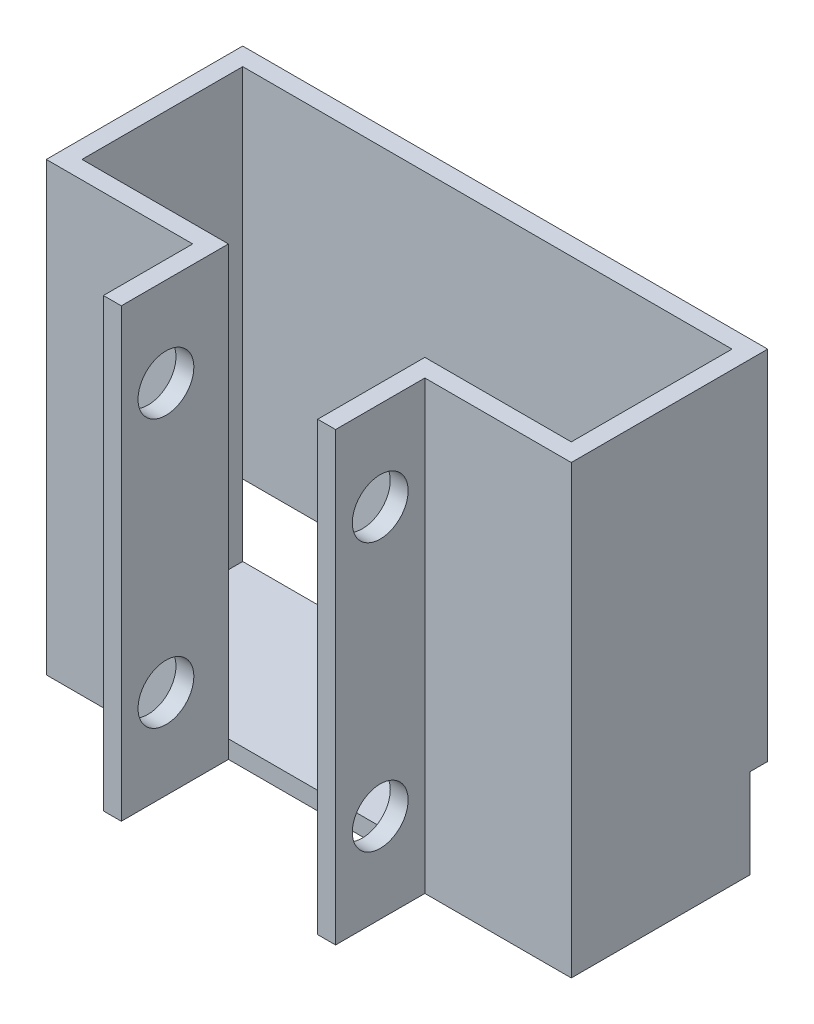
SolidWorks part; units mm, degrees
ref_plane "Front Plane" through (0, 0, 0) normal (0, 0, 1) x (1, 0, 0)
ref_plane "Top Plane" through (0, 0, 0) normal (0, 1, 0) x (1, 0, 0)
ref_plane "Right Plane" through (0, 0, 0) normal (1, 0, 0) x (0, 0, -1)
sketch "Sketch1" plane through (0, 0, 0) normal (0, 0, 1) x (1, 0, 0)
  line L1 (-35.9936, 30.5476) -> (38.6824, 30.5476)
  line L2 (-35.9936, 30.5476) -> (-35.9936, -32.9524)
  line L3 (-35.9936, -32.9524) -> (38.6824, -32.9524)
  line L4 (38.6824, 30.5476) -> (38.6824, -32.9524)
  dimension "D1" = 74.676
  dimension "D2" = 63.5
extrude "Boss-Extrude1" add sketch "Sketch1" along normal blind 27.94
sketch "Sketch2" plane through (0, 30.5476, 0) normal (0, 1, 0) x (1, 0, 0)
  line L0 (38.6824, 0) -> (-35.9936, 0) construction
  line L1 (36.1424, -25.4) -> (-33.4536, -25.4)
  line L2 (36.1424, -25.4) -> (36.1424, -2.54)
  line L3 (36.1424, -2.54) -> (-33.4536, -2.54)
  line L4 (-33.4536, -25.4) -> (-33.4536, -2.54)
  line L5 (-35.9936, -27.94) -> (-35.9936, 0) construction
  line L6 (38.6824, -27.94) -> (-35.9936, -27.94) construction
  line L7 (38.6824, -27.94) -> (38.6824, 0) construction
  dimension "D1" = 2.54
  dimension "D2" = 2.54
  dimension "D3" = 2.54
  dimension "D4" = 2.54
extrude "Cut-Extrude1" cut sketch "Sketch2" against normal blind 60.96
sketch "Sketch3" plane through (0, 0, 27.94) normal (0, 0, 1) x (1, 0, 0)
  line L0 (38.6824, 30.5476) -> (-35.9936, 30.5476) construction
  line L1 (-12.6256, 30.5476) -> (15.3144, 30.5476)
  line L2 (-12.6256, 30.5476) -> (-12.6256, -32.9524)
  line L3 (-12.6256, -32.9524) -> (15.3144, -32.9524)
  line L4 (15.3144, 30.5476) -> (15.3144, -32.9524)
  line L7 (38.6824, -32.9524) -> (38.6824, 30.5476) construction
  line L8 (-35.9936, -32.9524) -> (38.6824, -32.9524) construction
  dimension "D1" = 27.94
  dimension "D2" = 23.368
extrude "Cut-Extrude2" cut sketch "Sketch3" against normal blind 2.54
sketch "Sketch4" plane through (0, 0, 0) normal (0, 0, -1) x (-1, 0, 0)
  line L0 (35.9936, 30.5476) -> (35.9936, -32.9524) construction
  line L1 (-38.6824, -32.9524) -> (35.9936, -32.9524)
  line L2 (-38.6824, -32.9524) -> (-38.6824, -20.2524)
  line L3 (-38.6824, -20.2524) -> (35.9936, -20.2524)
  line L4 (35.9936, -32.9524) -> (35.9936, -20.2524)
  dimension "D1" = 12.7
extrude "Cut-Extrude3" cut sketch "Sketch4" against normal blind 2.54
sketch "Sketch5" plane through (0, 0, 27.94) normal (0, 0, 1) x (1, 0, 0)
  line L0 (-35.9936, -32.9524) -> (-12.6256, -32.9524) construction
  line L1 (-12.6256, 30.5476) -> (-15.1656, 30.5476)
  line L2 (-12.6256, 30.5476) -> (-12.6256, -32.9524)
  line L3 (-12.6256, -32.9524) -> (-15.1656, -32.9524)
  line L4 (-15.1656, 30.5476) -> (-15.1656, -32.9524)
  line L5 (15.3144, -32.9524) -> (38.6824, -32.9524) construction
  line L6 (15.3144, 30.5476) -> (17.8544, 30.5476)
  line L7 (15.3144, 30.5476) -> (15.3144, -32.9524)
  line L8 (15.3144, -32.9524) -> (17.8544, -32.9524)
  line L9 (17.8544, 30.5476) -> (17.8544, -32.9524)
  dimension "D1" = 2.54
  dimension "D2" = 2.54
extrude "Boss-Extrude2" add sketch "Sketch5" along normal blind 12.7
sketch "Sketch6" plane through (-15.1656, 0, 0) normal (-1, 0, 0) x (0, 0, 1)
  line L0 (40.64, 30.5476) -> (27.94, 30.5476) construction
  line L1 (40.64, 30.5476) -> (40.64, -32.9524) construction
  line L3 (40.64, -32.9524) -> (27.94, -32.9524) construction
  circle A0 centre (34.29, 17.8476) radius 3.9687
  circle A1 centre (34.29, -20.2524) radius 3.9687
  point P8 (0, 0)
  point P10 (33.6991, -32.9524)
  dimension "D1" = 12.7
  dimension "D2" = 6.35
  dimension "D3" = 6.35
  dimension "D4" = 12.7
extrude "Cut-Extrude4" cut sketch "Sketch6" against normal blind 50.8
